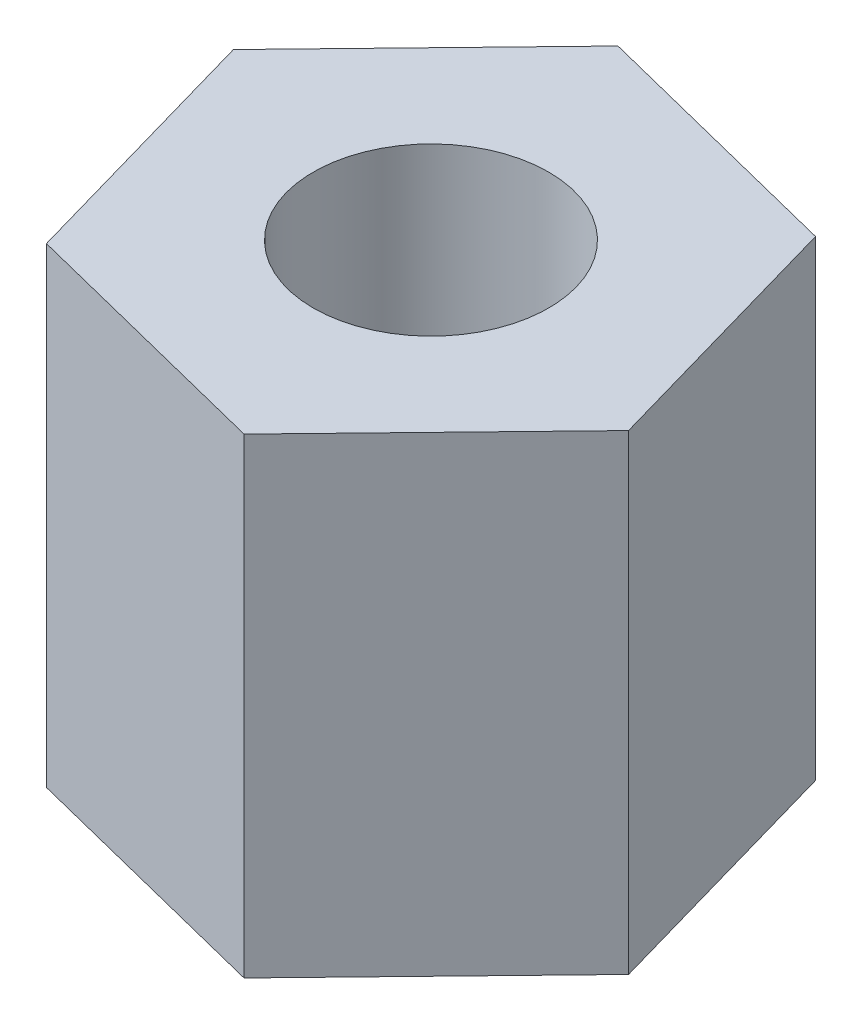
SolidWorks part; units mm, degrees
ref_plane "Alzado" through (0, 0, 0) normal (0, 0, 1) x (1, 0, 0)
ref_plane "Planta" through (0, 0, 0) normal (0, 1, 0) x (1, 0, 0)
ref_plane "Vista lateral" through (0, 0, 0) normal (1, 0, 0) x (0, 0, -1)
sketch "Croquis1" plane through (0, 0, 0) normal (0, 1, 0) x (1, 0, 0)
  line L1 (-5.5999, 1.405) -> (-4.0167, -4.1472)
  line L2 (-4.0167, -4.1472) -> (1.5832, -5.5522)
  line L3 (1.5832, -5.5522) -> (5.5999, -1.405)
  line L4 (5.5999, -1.405) -> (4.0167, 4.1472)
  line L5 (4.0167, 4.1472) -> (-1.5832, 5.5522)
  line L6 (-1.5832, 5.5522) -> (-5.5999, 1.405)
  circle A0 centre (0, 0) radius 5 construction
  circle A1 centre (0, 0) radius 2.5
  dimension "D2" = 5
  dimension "D1" = 10
extrude "Saliente-Extruir1" add sketch "Croquis1" along normal blind 10
